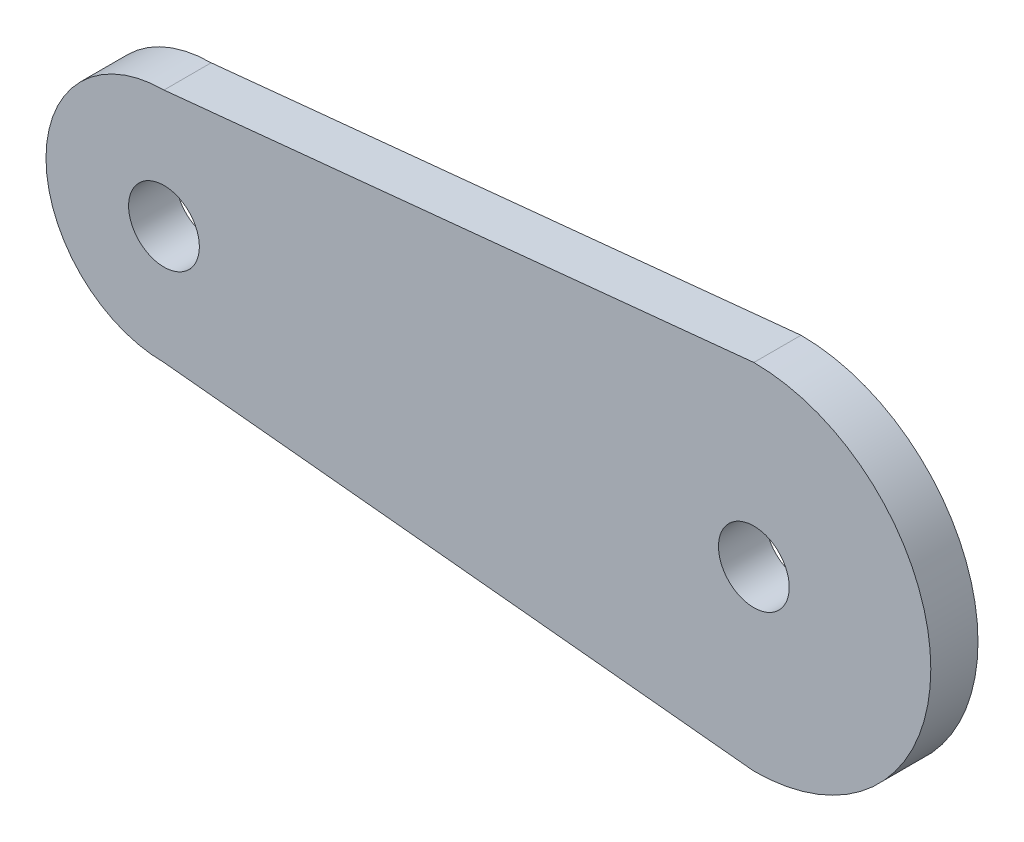
SolidWorks part; units mm, degrees
ref_plane "Front Plane" through (0, 0, 0) normal (0, 0, 1) x (1, 0, 0)
ref_plane "Top Plane" through (0, 0, 0) normal (0, 1, 0) x (1, 0, 0)
ref_plane "Right Plane" through (0, 0, 0) normal (1, 0, 0) x (0, 0, -1)
sketch "Sketch1" plane through (0, 0, 0) normal (0, 0, 1) x (1, 0, 0)
  line L0 (0, 0) -> (25, 2.5)
  line L1 (0, -10) -> (25, -12.5)
  line L2 (0, 0) -> (0, -10)
  line L3 (25, 2.5) -> (25, -12.5)
  line L4 (0, -5) -> (25, -5)
  arc A0 (0, 0) -> (0, -10) centre (0, -5) ccw
  arc A1 (25, 2.5) -> (25, -12.5) centre (25, -5) cw
  circle A2 centre (0, -5) radius 1.5
  circle A3 centre (25, -5) radius 1.5
  dimension "D2" = 15
  dimension "D1" = 25
  dimension "D3" = 10
extrude "Boss-Extrude1" add sketch "Sketch1" along normal blind 2 contours A3 L3 L0 L2 A2 L4 | A3 L4 A2 L2 L1 L3 | A3 L3 A1 | A2 L2 A0
